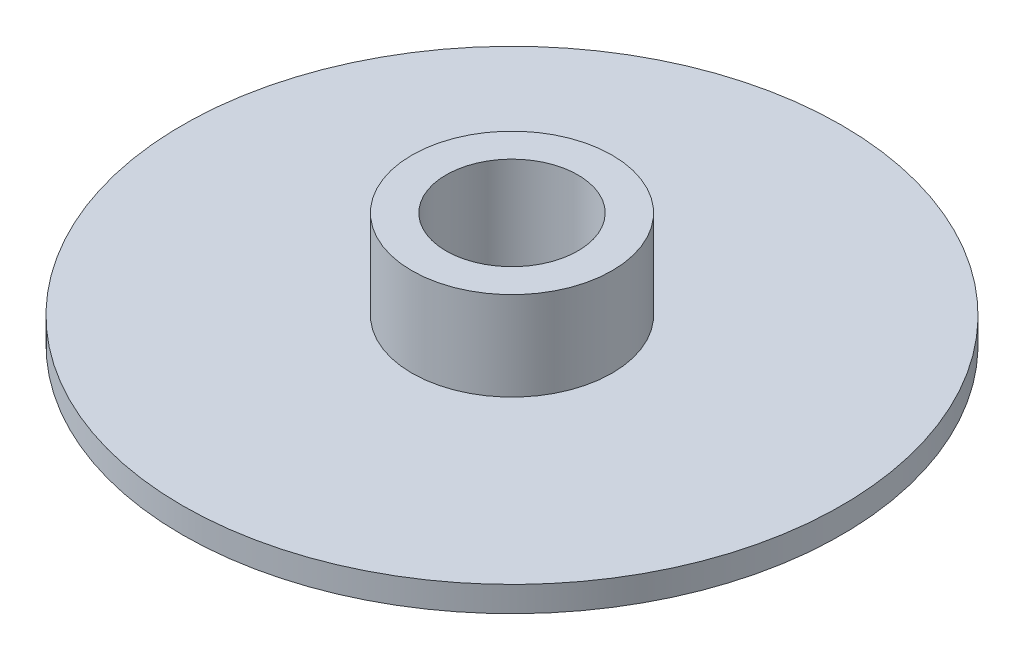
SolidWorks part; units mm, degrees
ref_plane "Alzado" through (0, 0, 0) normal (0, 0, 1) x (1, 0, 0)
ref_plane "Planta" through (0, 0, 0) normal (0, 1, 0) x (1, 0, 0)
ref_plane "Vista lateral" through (0, 0, 0) normal (1, 0, 0) x (0, 0, -1)
sketch "Croquis1" plane through (0, 0, 0) normal (0, 1, 0) x (1, 0, 0)
  circle A0 centre (0, 0) radius 13
  dimension "D1" = 26
extrude "Saliente-Extruir1" add sketch "Croquis1" along normal blind 1
sketch "Croquis2" plane through (0, 1, 0) normal (0, 1, 0) x (1, 0, 0)
  circle A0 centre (0, 0) radius 3.95
  dimension "D1" = 7.9
extrude "Saliente-Extruir2" add sketch "Croquis2" along normal blind 3.5
sketch "Croquis3" plane through (0, 4.5, 0) normal (0, 1, 0) x (1, 0, 0)
  circle A0 centre (0, 0) radius 2.6
  dimension "D1" = 5.2
extrude "Cortar-Extruir1" cut sketch "Croquis3" against normal through all
